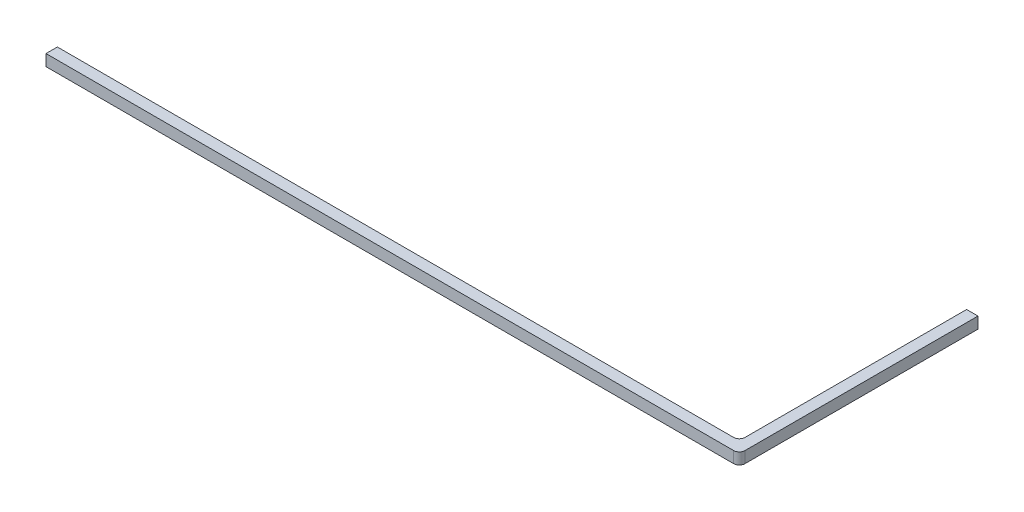
SolidWorks part; units mm, degrees
ref_plane "前视基准面" through (0, 0, 0) normal (0, 0, 1) x (1, 0, 0)
ref_plane "上视基准面" through (0, 0, 0) normal (0, 1, 0) x (1, 0, 0)
ref_plane "右视基准面" through (0, 0, 0) normal (1, 0, 0) x (0, 0, -1)
sketch "草图1" plane through (0, 0, 0) normal (0, 1, 0) x (1, 0, 0)
  line L0 (0, 0) -> (600, 0)
  line L1 (0, -10) -> (600, -10)
  line L2 (600, -10) -> (610, -10)
  line L3 (610, -10) -> (610, 200)
  line L4 (600, 0) -> (600, 200)
  line L5 (600, 200) -> (610, 200)
  line L6 (0, 0) -> (0, -10)
extrude "凸台-拉伸1" add sketch "草图1" along normal blind 10
fillet "圆角1" radius 5 1 edges at (600, 5, 0)
fillet "圆角2" radius 5 1 edges at (610, 5, 10)
